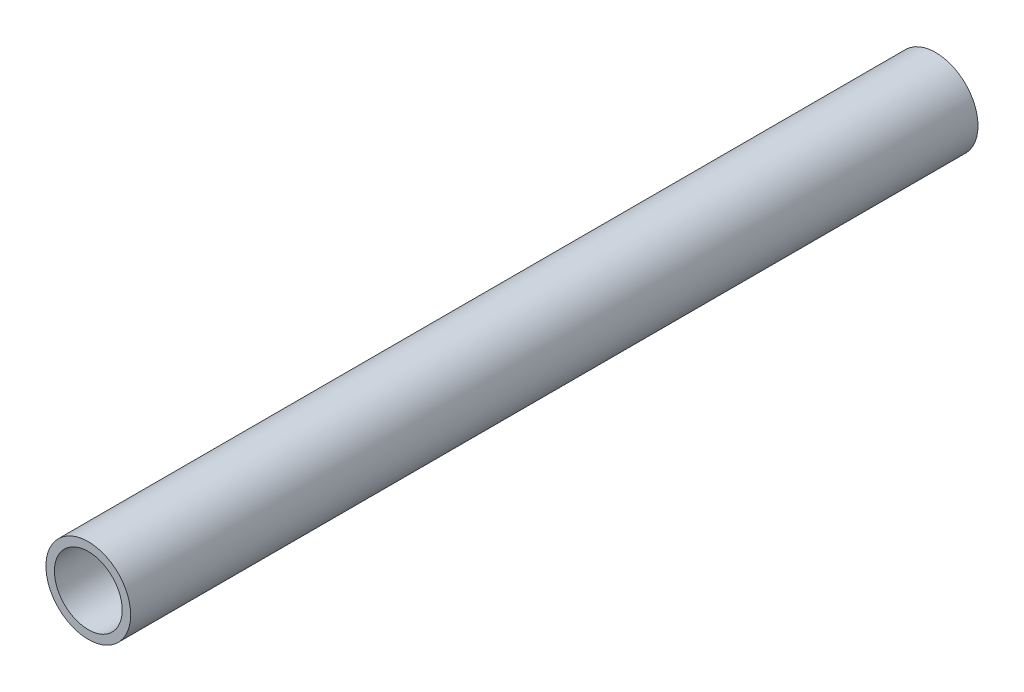
SolidWorks part; units mm, degrees
material "Thornel Mat VMA"
ref_plane "Płaszczyzna przednia" through (0, 0, 0) normal (0, 0, 1) x (1, 0, 0)
ref_plane "Płaszczyzna górna" through (0, 0, 0) normal (0, 1, 0) x (1, 0, 0)
ref_plane "Płaszczyzna prawa" through (0, 0, 0) normal (1, 0, 0) x (0, 0, -1)
sketch "Szkic1" plane through (0, 0, 0) normal (0, 0, 1) x (1, 0, 0)
  circle A0 centre (0, 0) radius 12
  circle A1 centre (0, 0) radius 15
  dimension "D1" = 3
  dimension "D2" = 30
extrude "Dodanie-wyciągnięcie1" add sketch "Szkic1" along normal blind 300
